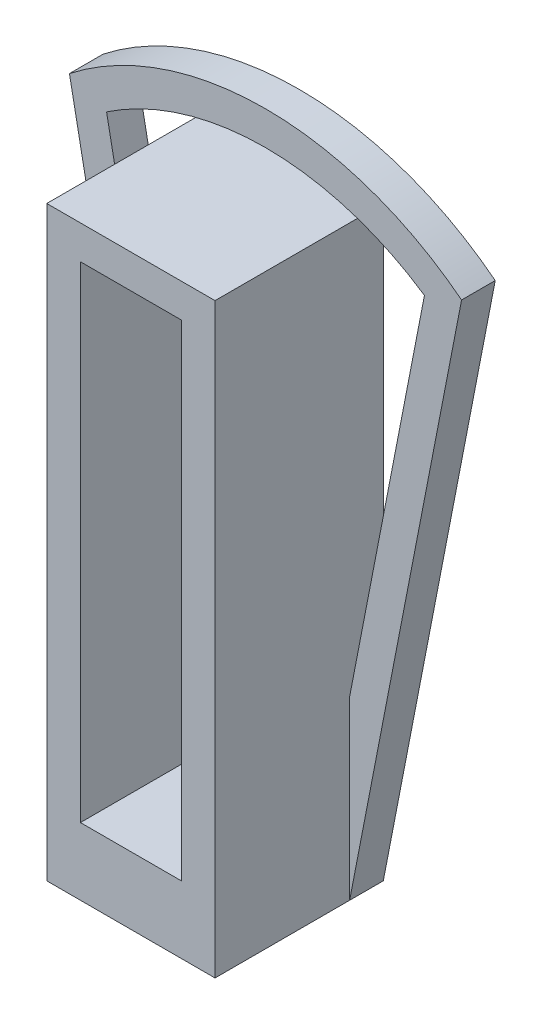
SolidWorks part; units mm, degrees
ref_plane "Front Plane" through (0, 0, 0) normal (0, 0, 1) x (1, 0, 0)
ref_plane "Top Plane" through (0, 0, 0) normal (0, 1, 0) x (1, 0, 0)
ref_plane "Right Plane" through (0, 0, 0) normal (1, 0, 0) x (0, 0, -1)
sketch "Sketch1" plane through (0, 0, 0) normal (0, 0, 1) x (1, 0, 0)
  line L0 (-0.5, -1.7) -> (-1.1652, 1.7224)
  line L1 (-0.5, -1.7) -> (0.5, -1.7)
  line L5 (-0.3351, -1.5) -> (-0.9446, 1.6356)
  line L6 (0.3351, -1.5) -> (0.9446, 1.6356)
  line L7 (0.5, -1.7) -> (1.1652, 1.7224)
  line L8 (-0.3351, -1.5) -> (0.3351, -1.5)
  line L9 (-0.5, -1.7) -> (-0.5, 2.2828) construction
  line L10 (0.5, -1.7) -> (0.5, 2.2828) construction
  arc A0 (-1.1652, 1.7224) -> (1.1652, 1.7224) centre (0, 0.2328) cw
  arc A1 (-0.9446, 1.6356) -> (0.9446, 1.6356) centre (0, 0.2328) cw
  point P0 (0, 0)
  dimension "D2" = 11
  dimension "D3" = 11
  dimension "D1" = 0.2
extrude "Boss-Extrude1" add sketch "Sketch1" along normal blind 0.2
sketch "Sketch3" plane through (0, 0, 0.2) normal (0, 0, 1) x (1, 0, 0)
  line L0 (-0.374, -1.3) -> (0.374, -1.3)
  line L1 (-0.9446, 1.6356) -> (-0.3351, -1.5) construction
  line L2 (0.3351, -1.5) -> (0.9446, 1.6356) construction
  line L3 (-0.5, -1.7) -> (0.5, -1.7) construction
  line L7 (-0.3351, -1.5) -> (0.3351, -1.5)
  line L8 (-0.9446, 1.6356) -> (-0.3351, -1.5)
  line L9 (0.3351, -1.5) -> (0.9446, 1.6356)
  line L10 (-0.3351, -1.5) -> (0.3351, -1.5)
  line L11 (-0.374, -1.3) -> (-0.3351, -1.5)
  line L12 (0.3351, -1.5) -> (0.374, -1.3)
  arc A1 (0.9446, 1.6356) -> (-0.9446, 1.6356) centre (0, 0.2328) ccw
  dimension "D1" = 0.4
  dimension "D2" = 0
extrude "Boss-Extrude2" add sketch "Sketch3" against normal up to surface (0.2 mm away) up to face at (0, 0.1116, 0)
sketch "Sketch4" plane through (0, 0, 0) normal (0, 0, 1) x (1, 0, 0)
  line L1 (-0.5, -1.7) -> (0.5, -1.7)
  line L2 (-0.5, -1.7) -> (-0.5, 1.7864)
  line L3 (-0.5, 1.7864) -> (0.5, 1.7864)
  line L4 (0.5, -1.7) -> (0.5, 1.7864)
  line L6 (-1.1652, 1.7224) -> (-0.5, -1.7) construction
  line L8 (-0.3, 1.5864) -> (0.3, 1.5864)
  line L9 (-0.3, 1.5864) -> (-0.3, -1.3)
  line L10 (-0.3, -1.3) -> (0.3, -1.3)
  line L11 (0.3, 1.5864) -> (0.3, -1.3)
  point P12 (0, 0)
  point P13 (0, 1.7864)
  dimension "D1" = 0.2
  dimension "D2" = 0.2
  dimension "D3" = 0.2
extrude "Boss-Extrude3" add sketch "Sketch4" along normal blind 1 separate body
equation "\"D3@Sketch1\"=\"D2@Sketch1\""
